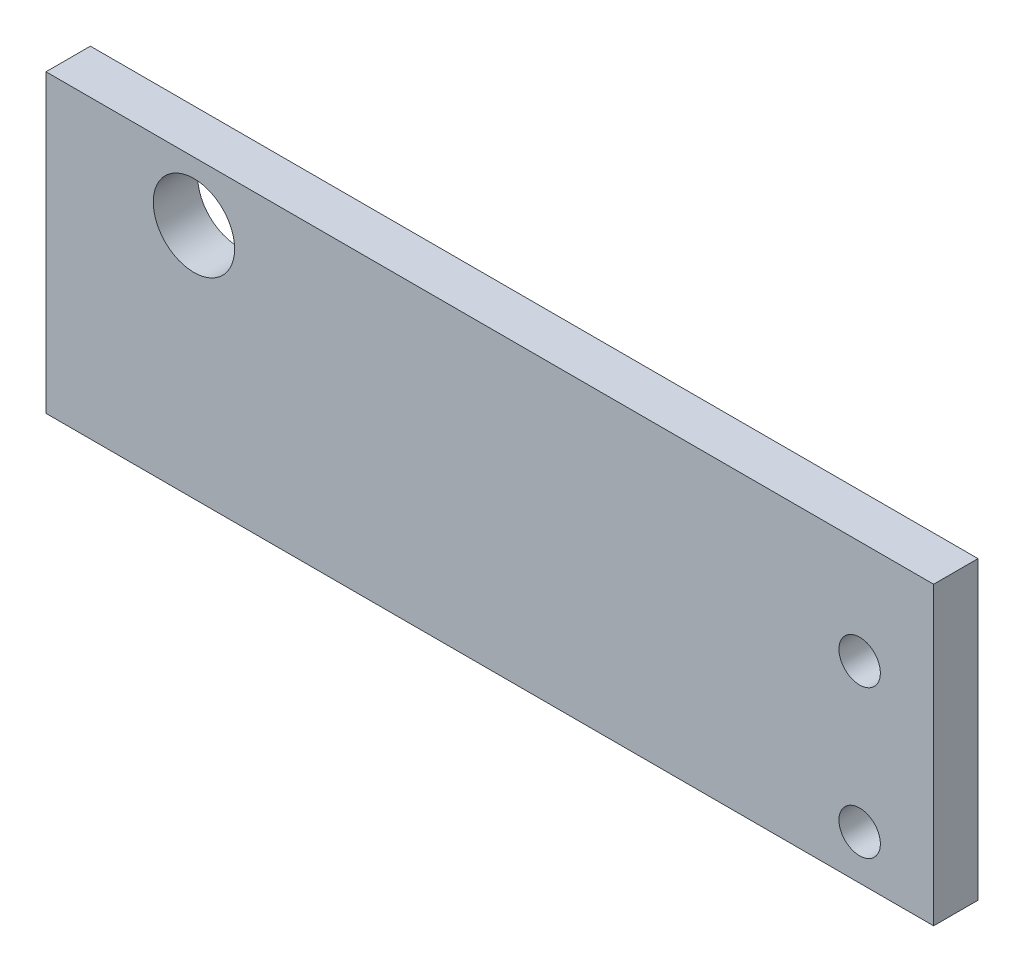
SolidWorks part; units mm, degrees
ref_plane "Front Plane" through (0, 0, 0) normal (0, 0, 1) x (1, 0, 0)
ref_plane "Top Plane" through (0, 0, 0) normal (0, 1, 0) x (1, 0, 0)
ref_plane "Right Plane" through (0, 0, 0) normal (1, 0, 0) x (0, 0, -1)
sketch "Sketch1" plane through (0, 0, 0) normal (0, 0, 1) x (1, 0, 0)
  line L1 (-24.3548, 15.9677) -> (35.6452, 15.9677)
  line L2 (-24.3548, 15.9677) -> (-24.3548, -4.0323)
  line L3 (-24.3548, -4.0323) -> (35.6452, -4.0323)
  line L4 (35.6452, 15.9677) -> (35.6452, -4.0323)
  circle A0 centre (-14.3548, 11.9677) radius 2.75
  circle A1 centre (30.6452, 8.9677) radius 1.4
  circle A2 centre (30.6452, -1.0323) radius 1.4
  dimension "D3" = 5.5
  dimension "D4" = 10
  dimension "D5" = 4
  dimension "D6" = 2.8
  dimension "D7" = 2.8
  dimension "D8" = 5
  dimension "D9" = 5
  dimension "D10" = 10
  dimension "D11" = 7
  dimension "D1" = 20
  dimension "D2" = 60
extrude "Boss-Extrude1" add sketch "Sketch1" along normal blind 3
